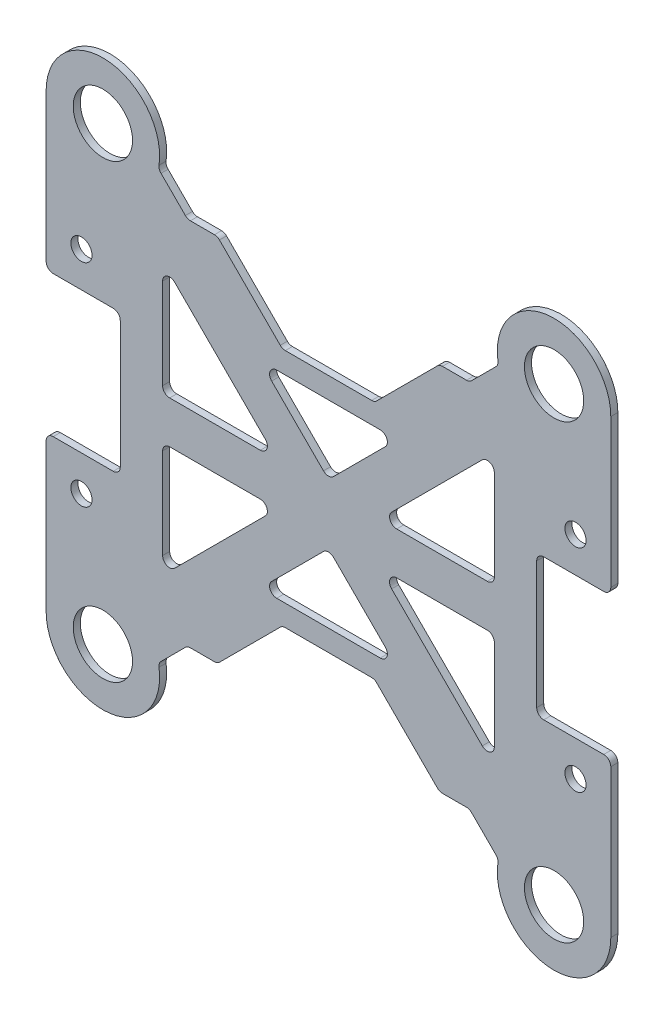
SolidWorks part; units mm, degrees
ref_plane "Спереди" through (0, 0, 0) normal (0, 0, 1) x (1, 0, 0)
ref_plane "Сверху" through (0, 0, 0) normal (0, 1, 0) x (1, 0, 0)
ref_plane "Справа" through (0, 0, 0) normal (1, 0, 0) x (0, 0, -1)
sketch "Model" plane through (0, 0, 0) normal (0, 0, 1) x (1, 0, 0)
  line L0 (-39, 10) -> (-30.5, 10)
  line L1 (-40, 15) -> (-40, 19)
  line L2 (-40, 15) -> (-40, 11)
  line L3 (0, 51) -> (0, -41) construction
  line L4 (-35, 0) -> (35, 0) construction
  line L5 (-40, 19) -> (-40, 31.9612)
  line L6 (-23.7246, 29.9471) -> (-20.2704, 26.4929)
  line L7 (-15.4419, 25.9071) -> (-6.8277, 17.2929)
  line L8 (-16.149, 26.2) -> (-19.5632, 26.2)
  line L9 (0, 17) -> (-6.1206, 17)
  line L10 (-29.5, 9) -> (-29.5, 0)
  line L11 (-22.5, 3) -> (-9.6569, 3)
  line L12 (-8.9497, 4.7071) -> (-21.7929, 17.5503)
  line L13 (-23.5, 6.7775) -> (-23.5, 16.8431)
  line L14 (-23.5, 6.7775) -> (-23.5, 4)
  line L15 (-22.5, 3) -> (-9.6569, 3)
  line L16 (-8.9497, 4.7071) -> (-21.7929, 17.5503)
  line L17 (-23.5, 4) -> (-23.5, 16.8431)
  line L18 (-23.5, 6.7775) -> (-23.5, 4)
  line L19 (0, 14) -> (-7.3431, 14)
  line L20 (-0.7071, 4.9497) -> (-8.0503, 12.2929)
  line L21 (39, 10) -> (30.5, 10)
  line L22 (40, 15) -> (40, 19)
  line L23 (40, 15) -> (40, 11)
  line L24 (40, 19) -> (40, 31.9612)
  line L25 (23.7246, 29.9471) -> (20.2704, 26.4929)
  line L26 (15.4419, 25.9071) -> (6.8277, 17.2929)
  line L27 (16.149, 26.2) -> (19.5632, 26.2)
  line L28 (0, 17) -> (6.1206, 17)
  line L29 (29.5, 9) -> (29.5, 0)
  line L30 (22.5, 3) -> (9.6569, 3)
  line L31 (8.9497, 4.7071) -> (21.7929, 17.5503)
  line L32 (23.5, 6.7775) -> (23.5, 16.8431)
  line L33 (23.5, 6.7775) -> (23.5, 4)
  line L34 (22.5, 3) -> (9.6569, 3)
  line L35 (8.9497, 4.7071) -> (21.7929, 17.5503)
  line L36 (23.5, 4) -> (23.5, 16.8431)
  line L37 (23.5, 6.7775) -> (23.5, 4)
  line L38 (0, 14) -> (7.3431, 14)
  line L39 (0.7071, 4.9497) -> (8.0503, 12.2929)
  line L40 (39, 10) -> (30.5, 10)
  line L41 (40, 15) -> (40, 19)
  line L42 (40, 15) -> (40, 11)
  line L43 (40, 19) -> (40, 31.9612)
  line L44 (23.7246, 29.9471) -> (20.2704, 26.4929)
  line L45 (15.4419, 25.9071) -> (6.8277, 17.2929)
  line L46 (16.149, 26.2) -> (19.5632, 26.2)
  line L47 (0, 17) -> (6.1206, 17)
  line L48 (29.5, 9) -> (29.5, 0)
  line L49 (22.5, 3) -> (9.6569, 3)
  line L50 (8.9497, 4.7071) -> (21.7929, 17.5503)
  line L51 (23.5, 6.7775) -> (23.5, 16.8431)
  line L52 (23.5, 6.7775) -> (23.5, 4)
  line L53 (22.5, 3) -> (9.6569, 3)
  line L54 (8.9497, 4.7071) -> (21.7929, 17.5503)
  line L55 (23.5, 4) -> (23.5, 16.8431)
  line L56 (23.5, 6.7775) -> (23.5, 4)
  line L57 (0, 14) -> (7.3431, 14)
  line L58 (0.7071, 4.9497) -> (8.0503, 12.2929)
  line L59 (-39, -10) -> (-30.5, -10)
  line L60 (-40, -15) -> (-40, -19)
  line L61 (-40, -15) -> (-40, -11)
  line L62 (-40, -19) -> (-40, -31.9612)
  line L63 (-23.7246, -29.9471) -> (-20.2704, -26.4929)
  line L64 (-15.4419, -25.9071) -> (-6.8277, -17.2929)
  line L65 (-16.149, -26.2) -> (-19.5632, -26.2)
  line L66 (0, -17) -> (-6.1206, -17)
  line L67 (-29.5, -9) -> (-29.5, 0)
  line L68 (-22.5, -3) -> (-9.6569, -3)
  line L69 (-8.9497, -4.7071) -> (-21.7929, -17.5503)
  line L70 (-23.5, -6.7775) -> (-23.5, -16.8431)
  line L71 (-23.5, -6.7775) -> (-23.5, -4)
  line L72 (-22.5, -3) -> (-9.6569, -3)
  line L73 (-8.9497, -4.7071) -> (-21.7929, -17.5503)
  line L74 (-23.5, -4) -> (-23.5, -16.8431)
  line L75 (-23.5, -6.7775) -> (-23.5, -4)
  line L76 (0, -14) -> (-7.3431, -14)
  line L77 (-0.7071, -4.9497) -> (-8.0503, -12.2929)
  line L78 (39, -10) -> (30.5, -10)
  line L79 (40, -15) -> (40, -19)
  line L80 (40, -15) -> (40, -11)
  line L81 (40, -19) -> (40, -31.9612)
  line L82 (23.7246, -29.9471) -> (20.2704, -26.4929)
  line L83 (15.4419, -25.9071) -> (6.8277, -17.2929)
  line L84 (16.149, -26.2) -> (19.5632, -26.2)
  line L85 (0, -17) -> (6.1206, -17)
  line L86 (29.5, -9) -> (29.5, 0)
  line L87 (22.5, -3) -> (9.6569, -3)
  line L88 (8.9497, -4.7071) -> (21.7929, -17.5503)
  line L89 (23.5, -6.7775) -> (23.5, -16.8431)
  line L90 (23.5, -6.7775) -> (23.5, -4)
  line L91 (22.5, -3) -> (9.6569, -3)
  line L92 (8.9497, -4.7071) -> (21.7929, -17.5503)
  line L93 (23.5, -4) -> (23.5, -16.8431)
  line L94 (23.5, -6.7775) -> (23.5, -4)
  line L95 (0, -14) -> (7.3431, -14)
  line L96 (0.7071, -4.9497) -> (8.0503, -12.2929)
  line L97 (0, 0) -> (0, 28.2) construction
  line L98 (0, 0) -> (0, -28.2) construction
  line L99 (0, 0) -> (-28.2, 0) construction
  line L100 (0, 0) -> (28.2, 0) construction
  line L101 (0, 0) -> (-54.5, 0) construction
  line L102 (0, 0) -> (54.5, 0) construction
  line L103 (0, 0) -> (0, -54.5) construction
  line L104 (0, 0) -> (0, 54.5) construction
  line L105 (-31.9612, 31.9612) -> (-38.1612, 31.9612) construction
  line L106 (-31.9612, 31.9612) -> (-25.7612, 31.9612) construction
  line L107 (-31.9612, 31.9612) -> (-31.9612, 38.1612) construction
  line L108 (-31.9612, 31.9612) -> (-31.9612, 25.7612) construction
  line L109 (31.9612, 31.9612) -> (38.1612, 31.9612) construction
  line L110 (31.9612, 31.9612) -> (25.7612, 31.9612) construction
  line L111 (31.9612, 31.9612) -> (31.9612, 38.1612) construction
  line L112 (31.9612, 31.9612) -> (31.9612, 25.7612) construction
  line L113 (31.9612, 31.9612) -> (38.1612, 31.9612) construction
  line L114 (31.9612, 31.9612) -> (25.7612, 31.9612) construction
  line L115 (31.9612, 31.9612) -> (31.9612, 38.1612) construction
  line L116 (31.9612, 31.9612) -> (31.9612, 25.7612) construction
  line L117 (-31.9612, -31.9612) -> (-38.1612, -31.9612) construction
  line L118 (-31.9612, -31.9612) -> (-25.7612, -31.9612) construction
  line L119 (-31.9612, -31.9612) -> (-31.9612, -38.1612) construction
  line L120 (-31.9612, -31.9612) -> (-31.9612, -25.7612) construction
  line L121 (31.9612, -31.9612) -> (38.1612, -31.9612) construction
  line L122 (31.9612, -31.9612) -> (25.7612, -31.9612) construction
  line L123 (31.9612, -31.9612) -> (31.9612, -38.1612) construction
  line L124 (31.9612, -31.9612) -> (31.9612, -25.7612) construction
  circle A0 centre (-35, 15) radius 1.5
  arc A1 (-29.5, 9) -> (-30.5, 10) centre (-30.5, 9) ccw
  circle A2 centre (-31.9612, 31.9612) radius 4.2
  arc A3 (-40, 11) -> (-39, 10) centre (-39, 11) ccw
  arc A4 (-24.0069, 30.7988) -> (-40, 31.9612) centre (-31.9612, 31.9612) ccw
  arc A5 (-24.0069, 30.7988) -> (-23.7246, 29.9471) centre (-23.0175, 30.6542) ccw
  arc A6 (-20.2704, 26.4929) -> (-19.5632, 26.2) centre (-19.5632, 27.2) ccw
  arc A7 (-15.4419, 25.9071) -> (-16.149, 26.2) centre (-16.149, 25.2) ccw
  arc A8 (-6.8277, 17.2929) -> (-6.1206, 17) centre (-6.1206, 18) ccw
  arc A9 (-21.7929, 17.5503) -> (-23.5, 16.8431) centre (-22.5, 16.8431) ccw
  arc A10 (-23.5, 4) -> (-22.5, 3) centre (-22.5, 4) ccw
  arc A11 (-9.6569, 3) -> (-8.9497, 4.7071) centre (-9.6569, 4) ccw
  arc A12 (-0.7071, 4.9497) -> (0, 4.6569) centre (0, 5.6569) ccw
  arc A13 (-7.3431, 14) -> (-8.0503, 12.2929) centre (-7.3431, 13) ccw
  circle A14 centre (35, 15) radius 1.5
  arc A15 (30.5, 10) -> (29.5, 9) centre (30.5, 9) ccw
  circle A16 centre (31.9612, 31.9612) radius 4.2
  arc A17 (39, 10) -> (40, 11) centre (39, 11) ccw
  arc A18 (40, 31.9612) -> (24.0069, 30.7988) centre (31.9612, 31.9612) ccw
  arc A19 (23.7246, 29.9471) -> (24.0069, 30.7988) centre (23.0175, 30.6542) ccw
  arc A20 (19.5632, 26.2) -> (20.2704, 26.4929) centre (19.5632, 27.2) ccw
  arc A21 (16.149, 26.2) -> (15.4419, 25.9071) centre (16.149, 25.2) ccw
  arc A22 (6.1206, 17) -> (6.8277, 17.2929) centre (6.1206, 18) ccw
  arc A23 (23.5, 16.8431) -> (21.7929, 17.5503) centre (22.5, 16.8431) ccw
  arc A24 (22.5, 3) -> (23.5, 4) centre (22.5, 4) ccw
  arc A25 (8.9497, 4.7071) -> (9.6569, 3) centre (9.6569, 4) ccw
  arc A26 (0, 4.6569) -> (0.7071, 4.9497) centre (0, 5.6569) ccw
  arc A27 (8.0503, 12.2929) -> (7.3431, 14) centre (7.3431, 13) ccw
  circle A28 centre (35, 15) radius 1.5
  arc A29 (30.5, 10) -> (29.5, 9) centre (30.5, 9) ccw
  circle A30 centre (31.9612, 31.9612) radius 4.2
  arc A31 (39, 10) -> (40, 11) centre (39, 11) ccw
  arc A32 (40, 31.9612) -> (24.0069, 30.7988) centre (31.9612, 31.9612) ccw
  arc A33 (23.7246, 29.9471) -> (24.0069, 30.7988) centre (23.0175, 30.6542) ccw
  arc A34 (19.5632, 26.2) -> (20.2704, 26.4929) centre (19.5632, 27.2) ccw
  arc A35 (16.149, 26.2) -> (15.4419, 25.9071) centre (16.149, 25.2) ccw
  arc A36 (6.1206, 17) -> (6.8277, 17.2929) centre (6.1206, 18) ccw
  arc A37 (23.5, 16.8431) -> (21.7929, 17.5503) centre (22.5, 16.8431) ccw
  arc A38 (22.5, 3) -> (23.5, 4) centre (22.5, 4) ccw
  arc A39 (8.9497, 4.7071) -> (9.6569, 3) centre (9.6569, 4) ccw
  arc A40 (0, 4.6569) -> (0.7071, 4.9497) centre (0, 5.6569) ccw
  arc A41 (8.0503, 12.2929) -> (7.3431, 14) centre (7.3431, 13) ccw
  circle A42 centre (-35, -15) radius 1.5
  arc A43 (-30.5, -10) -> (-29.5, -9) centre (-30.5, -9) ccw
  circle A44 centre (-31.9612, -31.9612) radius 4.2
  arc A45 (-39, -10) -> (-40, -11) centre (-39, -11) ccw
  arc A46 (-40, -31.9612) -> (-24.0069, -30.7988) centre (-31.9612, -31.9612) ccw
  arc A47 (-23.7246, -29.9471) -> (-24.0069, -30.7988) centre (-23.0175, -30.6542) ccw
  arc A48 (-19.5632, -26.2) -> (-20.2704, -26.4929) centre (-19.5632, -27.2) ccw
  arc A49 (-16.149, -26.2) -> (-15.4419, -25.9071) centre (-16.149, -25.2) ccw
  arc A50 (-6.1206, -17) -> (-6.8277, -17.2929) centre (-6.1206, -18) ccw
  arc A51 (-23.5, -16.8431) -> (-21.7929, -17.5503) centre (-22.5, -16.8431) ccw
  arc A52 (-22.5, -3) -> (-23.5, -4) centre (-22.5, -4) ccw
  arc A53 (-8.9497, -4.7071) -> (-9.6569, -3) centre (-9.6569, -4) ccw
  arc A54 (0, -4.6569) -> (-0.7071, -4.9497) centre (0, -5.6569) ccw
  arc A55 (-8.0503, -12.2929) -> (-7.3431, -14) centre (-7.3431, -13) ccw
  circle A56 centre (35, -15) radius 1.5
  arc A57 (29.5, -9) -> (30.5, -10) centre (30.5, -9) ccw
  circle A58 centre (31.9612, -31.9612) radius 4.2
  arc A59 (40, -11) -> (39, -10) centre (39, -11) ccw
  arc A60 (24.0069, -30.7988) -> (40, -31.9612) centre (31.9612, -31.9612) ccw
  arc A61 (24.0069, -30.7988) -> (23.7246, -29.9471) centre (23.0175, -30.6542) ccw
  arc A62 (20.2704, -26.4929) -> (19.5632, -26.2) centre (19.5632, -27.2) ccw
  arc A63 (15.4419, -25.9071) -> (16.149, -26.2) centre (16.149, -25.2) ccw
  arc A64 (6.8277, -17.2929) -> (6.1206, -17) centre (6.1206, -18) ccw
  arc A65 (21.7929, -17.5503) -> (23.5, -16.8431) centre (22.5, -16.8431) ccw
  arc A66 (23.5, -4) -> (22.5, -3) centre (22.5, -4) ccw
  arc A67 (9.6569, -3) -> (8.9497, -4.7071) centre (9.6569, -4) ccw
  arc A68 (0.7071, -4.9497) -> (0, -4.6569) centre (0, -5.6569) ccw
  arc A69 (7.3431, -14) -> (8.0503, -12.2929) centre (7.3431, -13) ccw
extrude "Бобышка-Вытянуть1" add sketch "Model" along normal blind 1 contours A64 L83 A63 L84 A62 L82 A61 A60 L81 L79 L80 A59 L78 A57 L86 L29 A15 L21 A17 L23 L22 L24 A18 A19 L25 A20 L27 A21 L26 A22 L28 L9 A8 L7 A7 L8 A6 L6 A5 A4 L5 L1 L2 A3 L0 A1 L10 L67 A43 L59 A45
